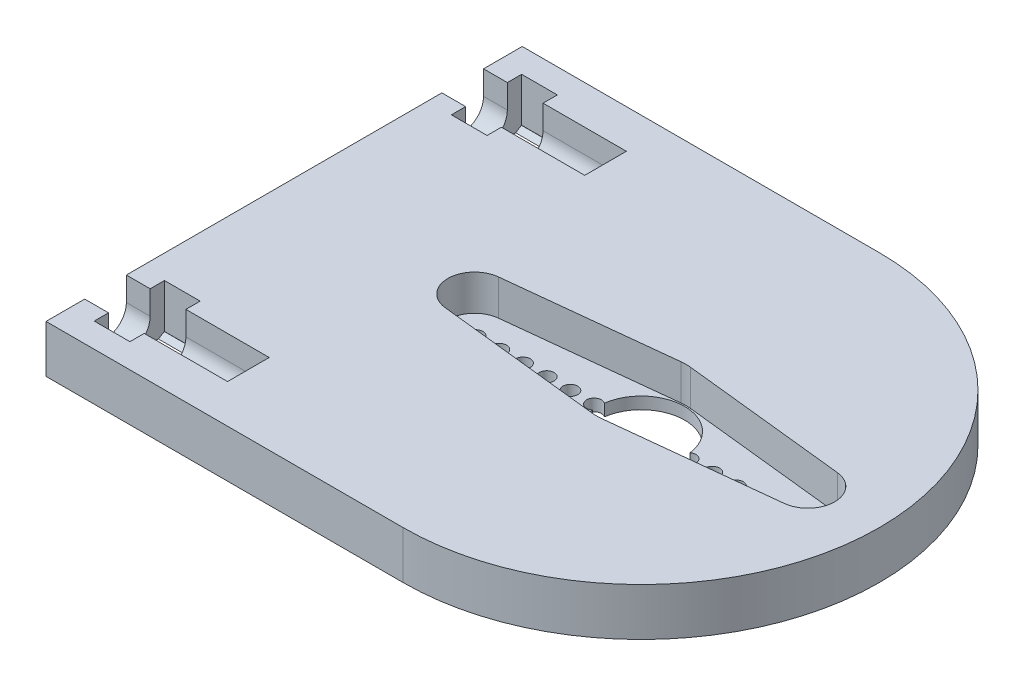
SolidWorks part; units mm, degrees
material "PLA"
ref_plane "Front Plane" through (0, 0, 0) normal (0, 0, 1) x (1, 0, 0)
ref_plane "Top Plane" through (0, 0, 0) normal (0, 1, 0) x (1, 0, 0)
ref_plane "Right Plane" through (0, 0, 0) normal (1, 0, 0) x (0, 0, -1)
sketch "Sketch1" plane through (0, 0, 0) normal (0, 1, 0) x (1, 0, 0)
  line L1 (-15, -20) -> (15, -20)
  line L2 (-15, -20) -> (-15, 20)
  line L3 (-15, 20) -> (15, 20)
  line L5 (-15, -20) -> (15, 20) construction
  line L6 (-15, 20) -> (15, -20) construction
  arc A0 (15, 20) -> (15, -20) centre (15, 0) cw
  point P0 (0, 0)
  dimension "D3" = 20
  dimension "D1" = 30
  dimension "D2" = 40
extrude "Boss-Extrude1" add sketch "Sketch1" along normal blind 4
sketch "Sketch2" plane through (0, 4, 0) normal (0, 1, 0) x (1, 0, 0)
  line L0 (-15, -20) -> (-15, -16.75) construction
  line L1 (-15, 20) -> (-15, -20) construction
  line L2 (-15, -16.75) -> (-15, -13.25)
  line L3 (-15, -13.25) -> (-13, -13.25)
  line L4 (-13, -13.25) -> (-13, -12.05)
  line L5 (-13, -12.05) -> (-10, -12.05)
  line L6 (-10, -12.05) -> (-10, -13.25)
  line L7 (-10, -13.25) -> (-3, -13.25)
  line L8 (-3, -13.25) -> (-3, -16.75)
  line L9 (-15, -15) -> (-3, -15) construction
  line L10 (-10, -16.75) -> (-3, -16.75)
  line L11 (-10, -17.95) -> (-10, -16.75)
  line L12 (-13, -17.95) -> (-10, -17.95)
  line L13 (-13, -16.75) -> (-13, -17.95)
  line L14 (-15, -16.75) -> (-13, -16.75)
  line L15 (-15, 0) -> (11.3005, 0) construction
  line L16 (-15, 15) -> (-3, 15) construction
  line L17 (-15, 16.75) -> (-13, 16.75)
  line L18 (-13, 16.75) -> (-13, 17.95)
  line L19 (-13, 17.95) -> (-10, 17.95)
  line L20 (-10, 17.95) -> (-10, 16.75)
  line L21 (-10, 16.75) -> (-3, 16.75)
  line L22 (-3, 13.25) -> (-3, 16.75)
  line L23 (-10, 13.25) -> (-3, 13.25)
  line L24 (-10, 12.05) -> (-10, 13.25)
  line L25 (-13, 12.05) -> (-10, 12.05)
  line L26 (-13, 13.25) -> (-13, 12.05)
  line L27 (-15, 13.25) -> (-13, 13.25)
  line L28 (-15, 16.75) -> (-15, 13.25)
  dimension "D1" = 2
  dimension "D3" = 1.2
  dimension "D4" = 7
  dimension "D5" = 3
  dimension "D6" = 3.5
  dimension "D7" = 3.25
extrude "Cut-Extrude1" cut sketch "Sketch2" against normal blind 2
sketch "Sketch3" plane through (-15, 0, 0) normal (-1, 0, 0) x (0, 0, 1)
  line L0 (16.75, 2) -> (13.25, 2) construction
  line L1 (13.25, 2) -> (16.75, 2) construction
  line L2 (13.25, 2) -> (16.75, 2)
  line L3 (0, -2.2) -> (0, 2.2) construction
  line L4 (-13.25, 2) -> (-16.75, 2)
  arc A0 (16.75, 2) -> (13.25, 2) centre (15, 2) cw
  arc A1 (-16.75, 2) -> (-13.25, 2) centre (-15, 2) ccw
extrude "Cut-Extrude2" cut sketch "Sketch3" against normal up to surface (12 mm away) up to face at (-3, 3, -15)
sketch "Sketch4" plane through (0, 4, 0) normal (0, 1, 0) x (1, 0, 0)
  line L1 (-13, 13.25) -> (-13, 12.05) construction
  line L2 (-13, 12.05) -> (-10, 12.05) construction
  line L3 (-10, 12.05) -> (-10, 13.25) construction
  line L5 (-10, 16.75) -> (-10, 17.95) construction
  line L6 (-10, 17.95) -> (-13, 17.95) construction
  line L7 (-13, 17.95) -> (-13, 16.75) construction
  line L9 (-13, 13.25) -> (-13, 12.05)
  line L10 (-13, 12.05) -> (-10, 12.05)
  line L11 (-10, 12.05) -> (-10, 13.25)
  line L13 (-10, 16.75) -> (-10, 17.95)
  line L14 (-10, 17.95) -> (-13, 17.95)
  line L15 (-13, 17.95) -> (-13, 16.75)
  line L16 (-13, 16.75) -> (-13, 13.25)
  line L17 (-10, 16.75) -> (-10, 13.25)
  line L18 (-2.2, 0) -> (2.2, 0) construction
  line L19 (-10, -16.75) -> (-10, -13.25)
  line L20 (-13, -16.75) -> (-13, -13.25)
  line L21 (-13, -17.95) -> (-13, -16.75)
  line L22 (-10, -17.95) -> (-13, -17.95)
  line L23 (-10, -16.75) -> (-10, -17.95)
  line L24 (-10, -12.05) -> (-10, -13.25)
  line L25 (-13, -12.05) -> (-10, -12.05)
  line L26 (-13, -13.25) -> (-13, -12.05)
extrude "Cut-Extrude3" cut sketch "Sketch4" against normal blind 3.7032
sketch "Sketch5" plane through (-10, 0, 0) normal (-1, 0, 0) x (0, 0, 1)
  line L0 (-17.95, 4) -> (-17.95, 0.3048) construction
  line L1 (-17.95, 0.3048) -> (-17.95, 0) construction
  line L2 (-20, 0) -> (20, 0) construction
  line L3 (-17.442, 0) -> (-12.558, 0)
  line L4 (-17.442, 0) -> (-17.95, 0.3048)
  line L5 (-15, 0) -> (-15, 5.9056) construction
  line L6 (-12.558, 0) -> (-12.05, 0.3048)
  line L7 (-17.95, 0.3048) -> (-12.05, 0.3048)
  line L8 (0, 0) -> (0, 9.0036) construction
  line L9 (12.558, 0) -> (12.05, 0.3048)
  line L10 (17.95, 0.3048) -> (12.05, 0.3048)
  line L11 (17.442, 0) -> (17.95, 0.3048)
  line L12 (17.442, 0) -> (12.558, 0)
  dimension "D1" = 0.3048
  dimension "D2" = 0.508
extrude "Cut-Extrude4" cut sketch "Sketch5" along normal up to surface (3 mm away) up to face at (-13, 2.0718, -17.0196)
sketch "Sketch6" plane through (0, 4, 0) normal (0, 1, 0) x (1, 0, 0)
  line L0 (-15, 20) -> (15, 20) construction
  line L1 (15, 20) -> (-15, 20) construction
  line L2 (15, 20) -> (15, -19.9991) construction
  line L3 (11.029, 0.6232) -> (9.0404, 0.6221) construction
  line L4 (10.9572, -0.0005) -> (10.9572, 0.619) construction
  line L5 (10.9572, 0.619) -> (10.9572, -0.524) construction
  line L6 (10.9572, -0.524) -> (11.3634, -0.524) construction
  line L7 (10.9572, 0.619) -> (10.9572, -0.2727) construction
  line L8 (10.9572, -0.2727) -> (10.4701, -0.2727) construction
  line L9 (9.0404, -0.6214) -> (11.029, -0.6214) construction
  line L10 (9.6622, -0.0005) -> (9.0404, 0.6221) construction
  line L11 (9.0404, 0.6221) -> (8.4288, -0.1114) construction
  line L12 (20.9596, 0.6221) -> (21.5712, -0.1114) construction
  line L13 (20.3378, -0.0005) -> (20.9596, 0.6221) construction
  line L14 (20.9596, -0.6214) -> (18.971, -0.6214) construction
  line L15 (19.0428, -0.2727) -> (19.5299, -0.2727) construction
  line L16 (18.971, 0.6232) -> (20.9596, 0.6221) construction
  line L17 (15, 0.0009) -> (18.971, 0.0009) construction
  line L18 (19.0428, 0.0009) -> (20.9596, 0.0003) construction
  line L19 (19.0428, 0.0009) -> (20.9596, 0.0009) construction
  line L20 (20.9596, 0.0009) -> (22.9482, 0.0009) construction
  line L21 (22.9482, 0.0009) -> (24.9368, 0.0003) construction
  line L22 (24.9368, 0.0003) -> (26.9254, 0.0009) construction
  line L23 (26.9254, 0.0009) -> (28.914, 0.0003) construction
  arc A0 (11.3949, -0.5025) -> (18.6051, -0.5025) centre (15, 0.0009) ccw
  arc A1 (11.3949, 0.5043) -> (11.3949, -0.5025) centre (11.029, 0.0009) ccw
  circle A2 centre (9.0404, 0.0003) radius 0.6218
  circle A3 centre (9.0404, 0.0009) radius 0.6223
  circle A4 centre (7.0518, 0.0003) radius 0.6218
  circle A5 centre (7.0518, 0.0009) radius 0.6223
  circle A6 centre (5.0632, 0.0003) radius 0.6218
  circle A7 centre (5.0632, 0.0009) radius 0.6223
  circle A8 centre (3.0746, 0.0003) radius 0.6218
  circle A9 centre (3.0746, 0.0009) radius 0.6223
  circle A10 centre (1.086, 0.0003) radius 0.6218
  circle A11 centre (28.914, 0.0003) radius 0.6218
  circle A12 centre (26.9254, 0.0009) radius 0.6223
  circle A13 centre (26.9254, 0.0003) radius 0.6218
  circle A14 centre (24.9368, 0.0009) radius 0.6223
  circle A15 centre (24.9368, 0.0003) radius 0.6218
  circle A16 centre (22.9482, 0.0009) radius 0.6223
  circle A17 centre (22.9482, 0.0003) radius 0.6218
  circle A18 centre (20.9596, 0.0009) radius 0.6223
  circle A19 centre (20.9596, 0.0003) radius 0.6218
  arc A20 (18.6051, 0.5043) -> (18.6051, -0.5025) centre (18.971, 0.0009) cw
  arc A21 (18.6051, 0.5043) -> (11.3949, 0.5043) centre (15, 0.0009) ccw
  dimension "D2" = 7.2801
  dimension "D14" = 1.2446
  dimension "D15" = 1.2436
  dimension "D1" = 30
  dimension "D3" = 4.0428
  dimension "D4" = 0.6195
  dimension "D5" = 1.143
  dimension "D6" = 0.4062
  dimension "D7" = 0.4872
  dimension "D9" = 0.6195
  dimension "D12" = 0.7335
extrude "Cut-Extrude5" cut sketch "Sketch6" against normal through all contours A20 A21 A1 A0 | A2 | A4 | A6 | A8 | A10 | A19 | A17 | A15 | A13 | A11
sketch "Sketch7" plane through (0, 4, 0) normal (0, 1, 0) x (1, 0, 0)
  line L0 (15, 0.0009) -> (14.5982, 3.7347) construction
  line L1 (15, 0.0009) -> (0.7589, 2.2379) construction
  line L2 (0.7589, 2.2379) -> (14.5982, 3.7347)
  line L3 (15, 0.0009) -> (32.6884, 0.0009) construction
  line L4 (15, 0.0009) -> (15, -11.7844) construction
  line L5 (0.7589, -2.2362) -> (14.5982, -3.7329)
  line L6 (29.2411, -2.2362) -> (15.4018, -3.7329)
  line L7 (29.2411, 2.2379) -> (15.4018, 3.7347)
  line L8 (0.7589, 2.2379) -> (-1.201, 0.4679) construction
  arc A0 (14.5982, 3.7347) -> (15.4018, 3.7347) centre (15, 0.0197) cw
  arc A1 (14.5982, -3.7329) -> (15.4018, -3.7329) centre (15, -0.018) ccw
  arc A2 (0.7589, 2.2379) -> (0.7589, -2.2362) centre (1, 0.0009) ccw
  arc A3 (29.2411, 2.2379) -> (29.2411, -2.2362) centre (29, 0.0009) cw
  dimension "D1" = 14.2411
  dimension "D2" = 2.2371
  dimension "D3" = 3.7338
  dimension "D4" = 0.4018
  dimension "D5" = 1.9599
  dimension "D6" = 1.7701
extrude "Cut-Extrude6" cut sketch "Sketch7" against normal blind 3
sketch "Sketch8" plane through (0, 0, 0) normal (0, -1, 0) x (1, 0, 0)
  line L0 (-15, 20) -> (-15, -20) construction
